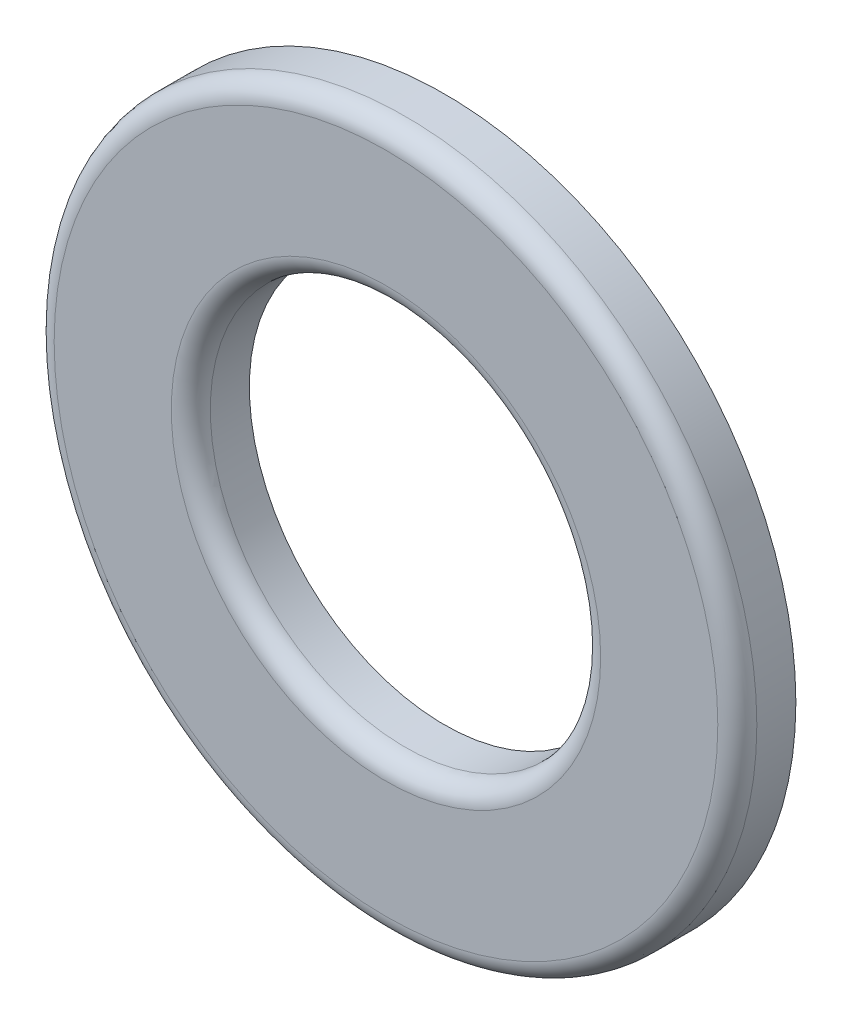
SolidWorks part; units mm, degrees
material "Chrome Stainless Steel"
ref_plane "Front Plane" through (0, 0, 0) normal (0, 0, 1) x (1, 0, 0)
ref_plane "Top Plane" through (0, 0, 0) normal (0, 1, 0) x (1, 0, 0)
ref_plane "Right Plane" through (0, 0, 0) normal (1, 0, 0) x (0, 0, -1)
sketch "Sketch1" plane through (0, 0, 0) normal (0, 0, 1) x (1, 0, 0)
  circle A0 centre (0, 0) radius 2.5
  circle A1 centre (0, 0) radius 4.5
  dimension "D1" = 5
  dimension "D2" = 9
extrude "Boss-Extrude1" add sketch "Sketch1" along normal blind 0.75
fillet "Fillet1" radius 0.25 2 edges at (2.5, 0, 0.75) (4.5, 0, 0.75)
